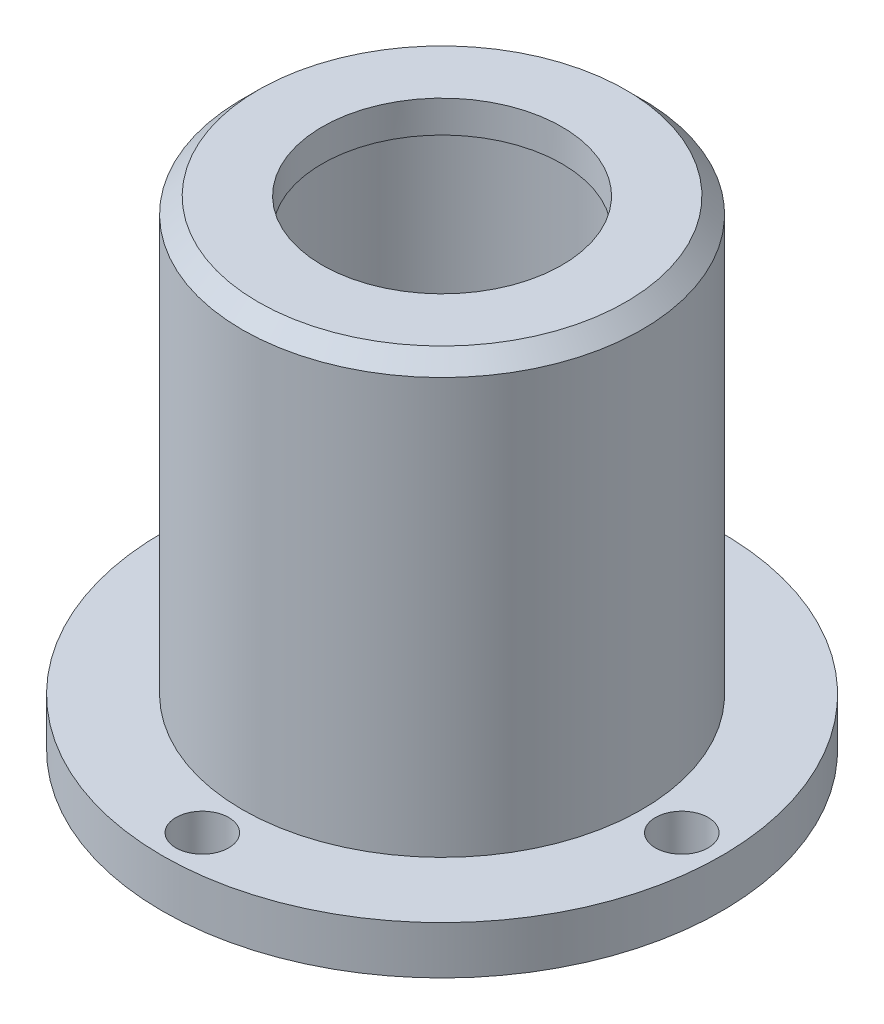
SolidWorks part; units mm, degrees
ref_plane "Спереди" through (0, 0, 0) normal (0, 0, 1) x (1, 0, 0)
ref_plane "Сверху" through (0, 0, 0) normal (0, 1, 0) x (1, 0, 0)
ref_plane "Справа" through (0, 0, 0) normal (1, 0, 0) x (0, 0, -1)
sketch "Эскиз1" plane through (0, 0, 0) normal (0, 1, 0) x (1, 0, 0)
  circle A0 centre (0, 0) radius 17.5
  dimension "D1" = 35
extrude "Бобышка-Вытянуть1" add sketch "Эскиз1" along normal blind 3
sketch "Эскиз2" plane through (0, 3, 0) normal (0, 1, 0) x (1, 0, 0)
  circle A0 centre (0, 0) radius 12.5
  dimension "D1" = 25
extrude "Бобышка-Вытянуть2" add sketch "Эскиз2" along normal blind 27
sketch "Эскиз4" plane through (0, 0, 0) normal (0, -1, 0) x (1, 0, 0)
  circle A0 centre (0, 0) radius 9.5
  dimension "D1" = 19
extrude "Вырез-Вытянуть1" cut sketch "Эскиз4" against normal blind 28
sketch "Эскиз5" plane through (0, 30, 0) normal (0, 1, 0) x (1, 0, 0)
  circle A0 centre (0, 0) radius 7.5
  dimension "D1" = 15
extrude "Вырез-Вытянуть2" cut sketch "Эскиз5" against normal blind 28
chamfer "Фаска1" distance 1 angle 45 1 edges at (0, 30, 12.5)
sketch "Эскиз6" plane through (0, 0, 0) normal (0, -1, 0) x (1, 0, 0)
  line L0 (0, 15) -> (0, -15) construction
  line L2 (15, 0) -> (-15, 0) construction
  circle A0 centre (0, 0) radius 15 construction
  circle A1 centre (0, 15) radius 1.65
  circle A2 centre (-15, 0) radius 1.65
  circle A3 centre (0, -15) radius 1.65
  circle A4 centre (15, 0) radius 1.65
  dimension "D1" = 30
  dimension "D2" = 3.3
  dimension "D3" = 3.3
  dimension "D4" = 3.3
  dimension "D5" = 3.3
extrude "Вырез-Вытянуть3" cut sketch "Эскиз6" against normal blind 10
